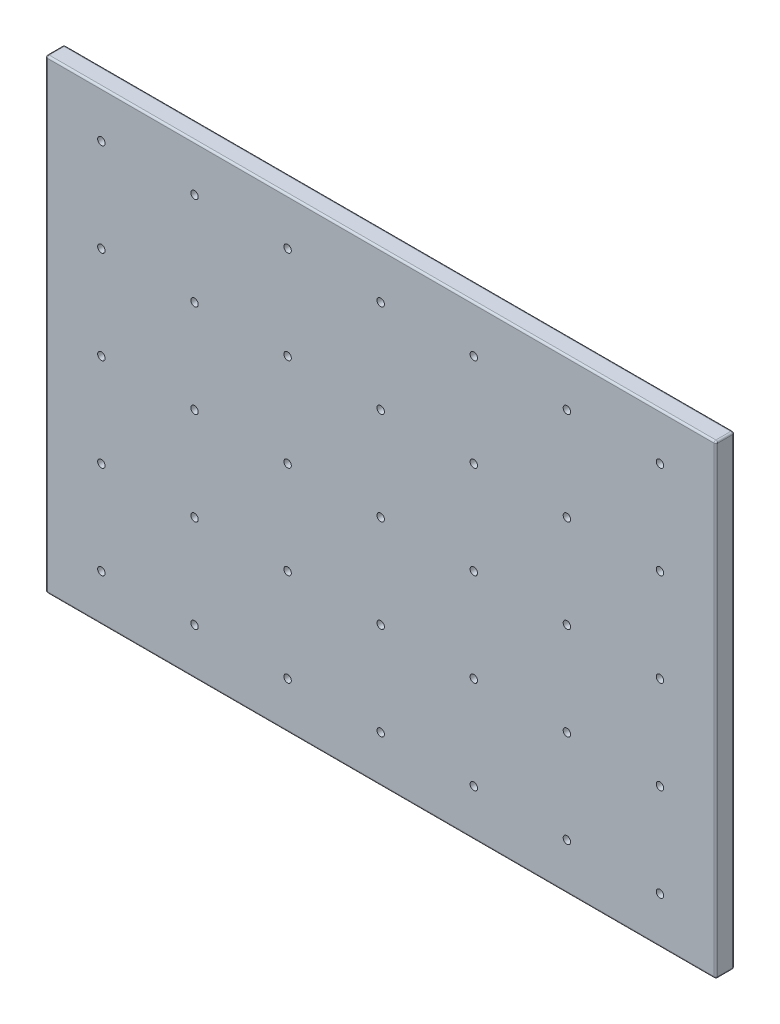
SolidWorks part; units mm, degrees
ref_plane "Front Plane" through (0, 0, 0) normal (0, 0, 1) x (1, 0, 0)
ref_plane "Top Plane" through (0, 0, 0) normal (0, 1, 0) x (1, 0, 0)
ref_plane "Right Plane" through (0, 0, 0) normal (1, 0, 0) x (0, 0, -1)
sketch "Sketch1" plane through (0, 0, 0) normal (0, 0, 1) x (1, 0, 0)
  line L0 (0, 0) -> (-179871.7364, 0) construction
  line L1 (0, 0) -> (0, 179871.7364) construction
  line L3 (360, -250) -> (-360, -250)
  line L4 (360, -250) -> (360, 250)
  line L5 (360, 250) -> (-360, 250)
  line L6 (-360, -250) -> (-360, 250)
  line L7 (360, -250) -> (-360, 250) construction
  line L8 (360, 250) -> (-360, -250) construction
  point P5 (0, 0)
  dimension "D1" = 720
  dimension "D2" = 500
extrude "Boss-Extrude1" add sketch "Sketch1" along normal blind 20
sketch "Sketch2" plane through (0, 0, 20) normal (0, 0, 1) x (1, 0, 0)
  line L0 (360, 250) -> (-360, 250) construction
  line L1 (-360, 250) -> (-360, -250) construction
  circle A0 centre (-300, 200) radius 4
  circle A1 centre (-200, 200) radius 4
  circle A2 centre (-100, 200) radius 4
  circle A3 centre (0, 200) radius 4
  circle A4 centre (100, 200) radius 4
  circle A5 centre (200, 200) radius 4
  circle A6 centre (300, 200) radius 4
  circle A7 centre (-200, 100) radius 4
  circle A8 centre (-100, 100) radius 4
  circle A9 centre (0, 100) radius 4
  circle A10 centre (100, 100) radius 4
  circle A11 centre (200, 100) radius 4
  circle A12 centre (300, 100) radius 4
  circle A13 centre (-200, 0) radius 4
  circle A14 centre (-100, 0) radius 4
  circle A15 centre (0, 0) radius 4
  circle A16 centre (100, 0) radius 4
  circle A17 centre (200, 0) radius 4
  circle A18 centre (300, 0) radius 4
  circle A19 centre (-200, -100) radius 4
  circle A20 centre (-100, -100) radius 4
  circle A21 centre (0, -100) radius 4
  circle A22 centre (100, -100) radius 4
  circle A23 centre (200, -100) radius 4
  circle A24 centre (300, -100) radius 4
  circle A25 centre (-200, -200) radius 4
  circle A26 centre (-100, -200) radius 4
  circle A27 centre (0, -200) radius 4
  circle A28 centre (100, -200) radius 4
  circle A29 centre (200, -200) radius 4
  circle A30 centre (300, -200) radius 4
  circle A31 centre (-300, 100) radius 4
  circle A32 centre (-300, 0) radius 4
  circle A33 centre (-300, -100) radius 4
  circle A34 centre (-300, -200) radius 4
  dimension "D1" = 8
  dimension "D2" = 50
  dimension "D3" = 60
  dimension "D4" = 7
  dimension "D5" = 5
extrude "Cut-Extrude1" cut sketch "Sketch2" against normal blind 10
fillet "Fillet1" radius 2 12 edges at (-360, 250, 10) (0, 250, 0) (0, 250, 20) (360, 250, 10) (360, 0, 0) (360, 0, 20) (360, -250, 10) (-360, 0, 0) (0, -250, 0) (-360, 0, 20) (0, -250, 20) (-360, -250, 10)
